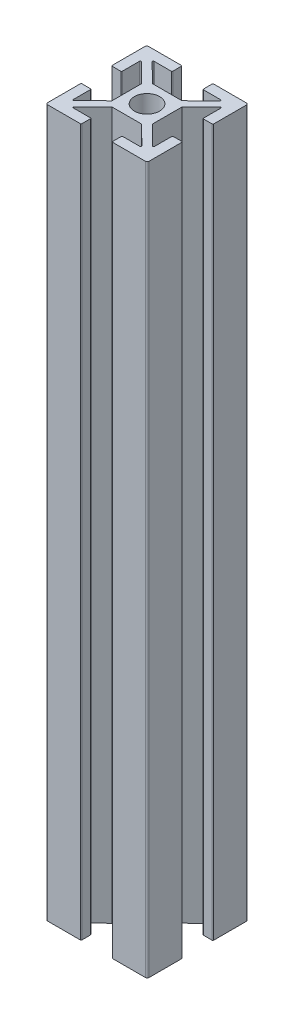
SolidWorks part; units mm, degrees
ref_plane "Front Plane" through (0, 0, 0) normal (0, 0, 1) x (1, 0, 0)
ref_plane "Top Plane" through (0, 0, 0) normal (0, 1, 0) x (1, 0, 0)
ref_plane "Right Plane" through (0, 0, 0) normal (1, 0, 0) x (0, 0, -1)
sketch "Sketch1" plane through (0, 0, 0) normal (0, 1, 0) x (1, 0, 0)
  line L0 (-9.8963, 3) -> (-8.1963, 3)
  line L3 (-3.1963, 10) -> (-9.6963, 10)
  line L4 (-10.0463, 3.15) -> (-10.0463, 9.65)
  line L7 (2.9332, 4) -> (-2.9332, 4)
  line L8 (-4, -2.9454) -> (-4, 2.9454)
  line L9 (-8.0463, 3.15) -> (-8.0463, 6.5862)
  line L10 (-6.6144, 8) -> (-3.1963, 8)
  line L11 (-3.0463, 8.15) -> (-3.0463, 9.85)
  line L12 (-8.0463, 8) -> (-4, 4) construction
  line L13 (-7.7908, 6.6929) -> (-4, 2.9454)
  line L14 (-6.7198, 7.7433) -> (-2.9332, 4)
  line L15 (8.0463, 8) -> (4, 4) construction
  line L22 (0, 0) -> (0, 11.6886) construction
  line L25 (0, 0) -> (-14.9841, 0) construction
  line L27 (6.7198, 7.7433) -> (2.9332, 4)
  line L28 (7.7908, 6.6929) -> (4, 2.9454)
  line L46 (3.0463, 8.15) -> (3.0463, 9.85)
  line L47 (6.6144, 8) -> (3.1963, 8)
  line L48 (8.0463, 3.15) -> (8.0463, 6.5862)
  line L49 (4, -2.9454) -> (4, 2.9454)
  line L50 (10.0463, 3.15) -> (10.0463, 9.65)
  line L51 (3.1963, 10) -> (9.6963, 10)
  line L52 (9.8963, 3) -> (8.1963, 3)
  line L53 (8.0463, -8) -> (4, -4) construction
  line L54 (-8.0463, -8) -> (-4, -4) construction
  line L55 (9.8963, -3) -> (8.1963, -3)
  line L56 (3.1963, -10) -> (9.6963, -10)
  line L57 (10.0463, -3.15) -> (10.0463, -9.65)
  line L58 (8.0463, -3.15) -> (8.0463, -6.5862)
  line L59 (6.6144, -8) -> (3.1963, -8)
  line L60 (3.0463, -8.15) -> (3.0463, -9.85)
  line L61 (7.7908, -6.6929) -> (4, -2.9454)
  line L62 (6.7198, -7.7433) -> (2.9332, -4)
  line L63 (-6.7198, -7.7433) -> (-2.9332, -4)
  line L64 (-7.7908, -6.6929) -> (-4, -2.9454)
  line L65 (-3.0463, -8.15) -> (-3.0463, -9.85)
  line L66 (-6.6144, -8) -> (-3.1963, -8)
  line L67 (-8.0463, -3.15) -> (-8.0463, -6.5862)
  line L68 (2.9332, -4) -> (-2.9332, -4)
  line L69 (-10.0463, -3.15) -> (-10.0463, -9.65)
  line L70 (-3.1963, -10) -> (-9.6963, -10)
  line L71 (-9.8963, -3) -> (-8.1963, -3)
  circle A0 centre (0, 0) radius 2.5
  arc A1 (-10.0463, 9.65) -> (-9.6963, 10) centre (-9.6963, 9.65) cw
  arc A2 (-9.8963, 3) -> (-10.0463, 3.15) centre (-9.8963, 3.15) cw
  arc A3 (-8.1963, 3) -> (-8.0463, 3.15) centre (-8.1963, 3.15) ccw
  arc A4 (-3.1963, 10) -> (-3.0463, 9.85) centre (-3.1963, 9.85) cw
  arc A5 (-3.1963, 8) -> (-3.0463, 8.15) centre (-3.1963, 8.15) ccw
  arc A6 (-6.7198, 7.7433) -> (-6.6144, 8) centre (-6.6144, 7.85) cw
  arc A7 (-7.7908, 6.6929) -> (-8.0463, 6.5862) centre (-7.8963, 6.5862) ccw
  arc A8 (7.7908, 6.6929) -> (8.0463, 6.5862) centre (7.8963, 6.5862) cw
  arc A9 (6.7198, 7.7433) -> (6.6144, 8) centre (6.6144, 7.85) ccw
  arc A10 (3.1963, 8) -> (3.0463, 8.15) centre (3.1963, 8.15) cw
  arc A11 (3.1963, 10) -> (3.0463, 9.85) centre (3.1963, 9.85) ccw
  arc A12 (8.1963, 3) -> (8.0463, 3.15) centre (8.1963, 3.15) cw
  arc A13 (9.8963, 3) -> (10.0463, 3.15) centre (9.8963, 3.15) ccw
  arc A14 (10.0463, 9.65) -> (9.6963, 10) centre (9.6963, 9.65) ccw
  arc A15 (10.0463, -9.65) -> (9.6963, -10) centre (9.6963, -9.65) cw
  arc A16 (9.8963, -3) -> (10.0463, -3.15) centre (9.8963, -3.15) cw
  arc A17 (8.1963, -3) -> (8.0463, -3.15) centre (8.1963, -3.15) ccw
  arc A18 (3.1963, -10) -> (3.0463, -9.85) centre (3.1963, -9.85) cw
  arc A19 (3.1963, -8) -> (3.0463, -8.15) centre (3.1963, -8.15) ccw
  arc A20 (6.7198, -7.7433) -> (6.6144, -8) centre (6.6144, -7.85) cw
  arc A21 (7.7908, -6.6929) -> (8.0463, -6.5862) centre (7.8963, -6.5862) ccw
  arc A22 (-7.7908, -6.6929) -> (-8.0463, -6.5862) centre (-7.8963, -6.5862) cw
  arc A23 (-6.7198, -7.7433) -> (-6.6144, -8) centre (-6.6144, -7.85) ccw
  arc A24 (-3.1963, -8) -> (-3.0463, -8.15) centre (-3.1963, -8.15) cw
  arc A25 (-3.1963, -10) -> (-3.0463, -9.85) centre (-3.1963, -9.85) ccw
  arc A26 (-8.1963, -3) -> (-8.0463, -3.15) centre (-8.1963, -3.15) cw
  arc A27 (-9.8963, -3) -> (-10.0463, -3.15) centre (-9.8963, -3.15) ccw
  arc A28 (-10.0463, -9.65) -> (-9.6963, -10) centre (-9.6963, -9.65) ccw
  point P8 (-10.0463, 10)
  point P27 (-10.0463, 3)
  point P30 (3.0463, 8)
  point P31 (10.0463, -10)
  point P50 (4, 0)
  point P55 (-8.0463, 3)
  point P58 (-3.0463, 10)
  point P61 (-3.0463, 8)
  point P63 (0, 4)
  point P65 (3.0463, 10)
  point P66 (8.0463, 3)
  point P67 (10.0463, 3)
  point P68 (10.0463, 10)
  point P118 (-4, 0)
  point P119 (10.0463, -3)
  point P120 (8.0463, -3)
  point P121 (3.0463, -10)
  point P122 (0, -4)
  point P123 (-3.0463, -8)
  point P124 (-3.0463, -10)
  point P125 (-8.0463, -3)
  point P126 (3.0463, -8)
  point P127 (-10.0463, -3)
  point P128 (-10.0463, -10)
  dimension "D2" = 0.35
  dimension "D3" = 0.15
  dimension "D4" = 0.15
  dimension "D5" = 0.15
  dimension "D12" = 0.15
  dimension "D13" = 0.15
  dimension "D14" = 0.15
  dimension "D6" = 2
  dimension "D7" = 7
  dimension "D8" = 7
  dimension "D9" = 2
  dimension "D10" = 0.75
  dimension "D11" = 0.75
extrude "Boss-Extrude2" add sketch "Sketch1" along normal blind 140
